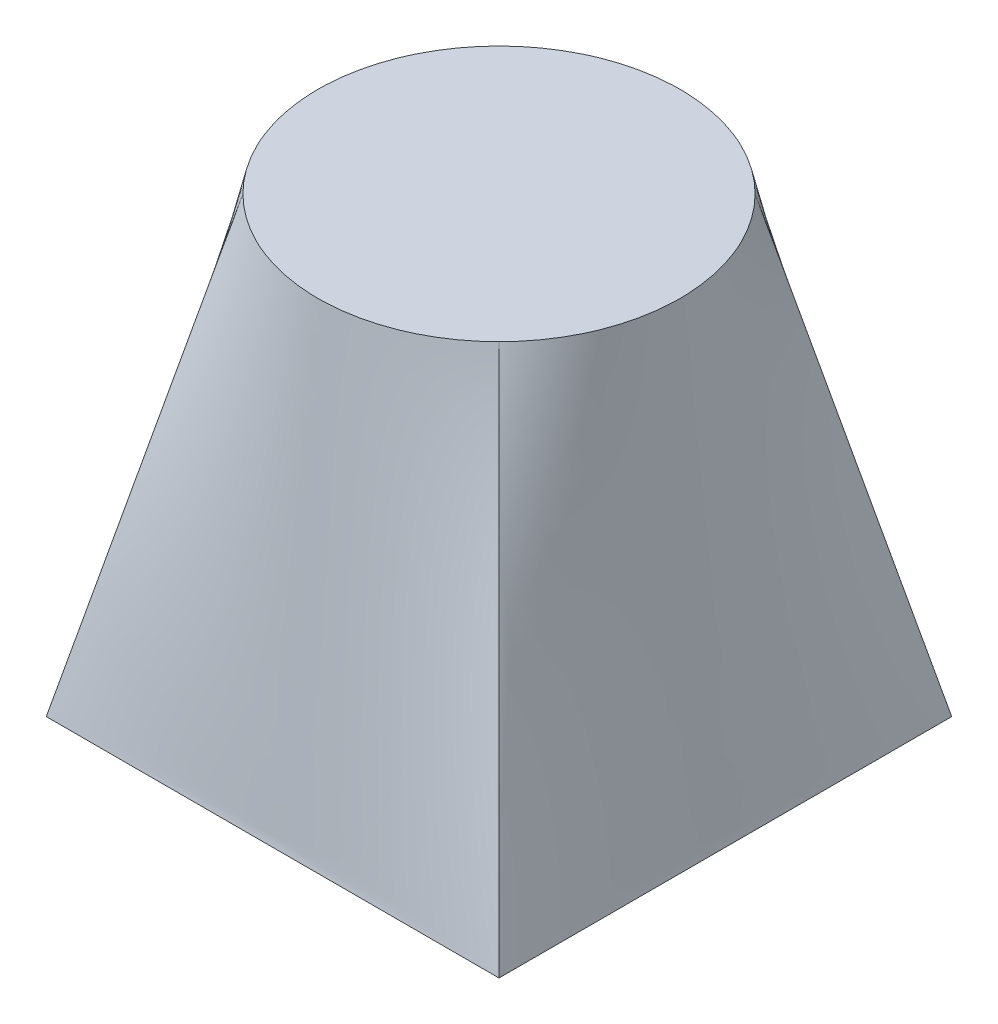
SolidWorks part; units mm, degrees
ref_plane "Front Plane" through (0, 0, 0) normal (0, 0, 1) x (1, 0, 0)
ref_plane "Top Plane" through (0, 0, 0) normal (0, 1, 0) x (1, 0, 0)
ref_plane "Right Plane" through (0, 0, 0) normal (1, 0, 0) x (0, 0, -1)
sketch "Sketch1" plane through (0, 0, 0) normal (0, 1, 0) x (1, 0, 0)
  line L1 (-5, -5) -> (5, -5)
  line L2 (-5, -5) -> (-5, 5)
  line L3 (-5, 5) -> (5, 5)
  line L4 (5, -5) -> (5, 5)
  line L5 (-5, -5) -> (5, 5) construction
  line L6 (-5, 5) -> (5, -5) construction
  point P0 (0, 0)
ref_plane "Plane1" through (0, 10, 0) normal (0, 1, 0) x (1, 0, 0)
sketch "Sketch2" plane through (0, 10, 0) normal (0, 1, 0) x (1, 0, 0)
  circle A0 centre (0, 0) radius 4
loft "Loft1" add profiles "Sketch1", "Sketch2"
